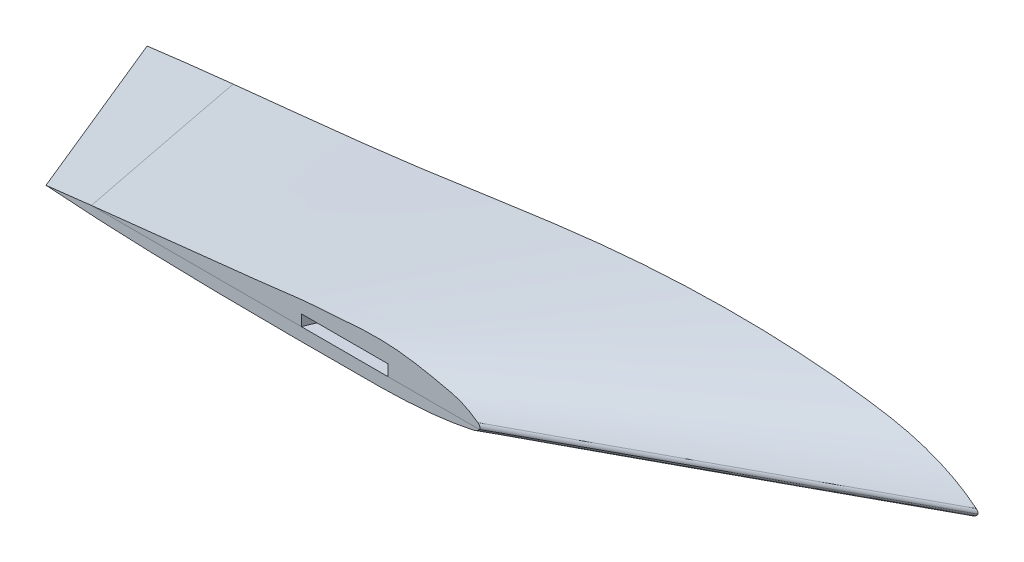
SolidWorks part; units mm, degrees
material "EPS 1.5lb"
ref_plane "Front Plane" through (0, 0, 0) normal (0, 0, 1) x (1, 0, 0)
ref_plane "Top Plane" through (0, 0, 0) normal (0, 1, 0) x (1, 0, 0)
ref_plane "Right Plane" through (0, 0, 0) normal (1, 0, 0) x (0, 0, -1)
sketch "Sketch1" plane through (0, 0, 0) normal (0, 0, 1) x (1, 0, 0)
  spline S3 degree 3 poles (-353.0971, 3.7664) (-263.6099, 15.4897) (-103.4056, 27.7025) (139.6254, 69.7319) (320.6009, 70.898) (447.0294, 49.1568) (484.462, 32.3978) (505.2254, 13.2914) knots 0 0 0 0 0.308402 0.542913 0.85017 0.887176 1 1 1 1
  spline S4 degree 3 poles (-353.0971, 3.7664) (-171.2042, -8.6227) (70.6812, -17.727) (367.6345, -8.5893) (467.935, -1.6347) (505.2254, 13.2914) knots 0 0 0 0 0.625313 0.861779 1 1 1 1
ref_plane "Plane1" through (0, 0, 180.975) normal (0, 0, 1) x (1, 0, 0)
sketch "Sketch2" plane through (0, 0, 180.975) normal (0, 0, 1) x (1, 0, 0)
  ellipse E1 centre (137.6249, -20.0426) end of major axis (189.6794, -20.0426) minor radius 48.2641 (175.2698, 13.2914) -> (153.373, 25.9598) ccw construction
  spline S0 degree 3 poles (-276.1301, 8.6931) (-231.4597, 13.8922) (-160.6069, 22.0458) (-55.2186, 32.8482) (-5.4847, 39.5878) (20.2948, 40.7341) (52.2153, 43.3112) (77.4334, 43.8548) (107.6579, 39.591) (131.1314, 34.7665) (149.4992, 30.2941) (163.4187, 23.0591) (171.5303, 16.9219) (175.2698, 13.2914) knots 0 0 0 0 0.247404 0.462109 0.504395 0.627983 0.653402 0.743134 0.818761 0.882434 0.92418 0.960505 1 1 1 1
  spline S4 degree 3 poles (-276.1301, 8.6931) (-174.261, 0.9112) (-23.6694, 0.6839) (127.5151, 0.6814) (175.2698, 13.2914) knots 0 0 0 0 0.676464 1 1 1 1
loft "Loft1" add profiles "Sketch1", "Sketch2"
fillet "Fillet3" radius 6.35 1 edges at (340.2476, 13.2914, 90.4875)
ref_plane "Plane2" through (0, 19.812, 0) normal (0, 1, 0) x (1, 0, 0)
sketch "Sketch7" plane through (0, 19.812, 0) normal (0, 1, 0) x (1, 0, 0)
  line L0 (148.5529, 0) -> (59.6529, 0)
  line L1 (59.6529, 0) -> (-13.4658, -180.975)
  line L2 (-13.4658, -180.975) -> (75.4342, -180.975)
  line L3 (75.4342, -180.975) -> (148.5529, 0)
  line L4 (-48.7437, -180.975) -> (48.7437, -180.975) construction
  line L5 (-48.7437, 0) -> (48.7437, 0) construction
  dimension "D1" = 68
  dimension "D2" = 88.9
  dimension "D3" = 501.65
  dimension "D4" = 88.9
extrude "Cut-Extrude1" cut sketch "Sketch7" against normal mid plane 11.43
sketch "Sketch8" plane through (0, 0, 0) normal (0, 1, 0) x (1, 0, 0)
  line L0 (-276.1301, -180.975) -> (-353.0971, 0) construction
  line L1 (-276.1301, -180.975) -> (167.9966, -180.975) construction
  line L2 (-276.1301, -180.975) -> (-328.3189, -58.2617)
  line L3 (-276.1301, -180.975) -> (-171.2438, -180.975)
  line L4 (-171.2438, -180.975) -> (-239.4979, -20.487)
  line L5 (-239.4979, -20.487) -> (-328.3189, -58.2617)
  dimension "D1" = 133.35
  dimension "D2" = 96.52
extrude "Cut-Extrude2" [suppressed] cut sketch "Sketch8" along normal through all and the other way through all contours L4 L5 L2 L3
ref_plane "Plane3" through (0, 14.097, 0) normal (0, 1, 0) x (1, 0, 0)
split "Split1" trim tools "Plane3" bodies to split 104 resulting bodies 106 107
